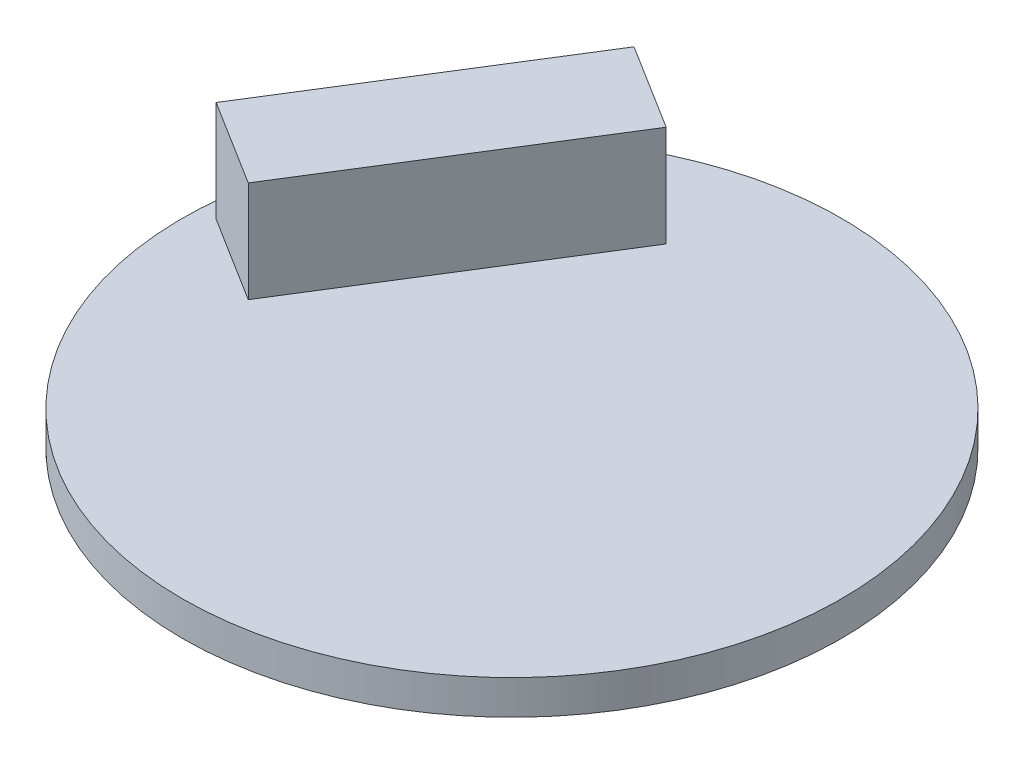
SolidWorks part; units mm, degrees
ref_plane "Front Plane" through (0, 0, 0) normal (0, 0, 1) x (1, 0, 0)
ref_plane "Top Plane" through (0, 0, 0) normal (0, 1, 0) x (1, 0, 0)
ref_plane "Right Plane" through (0, 0, 0) normal (1, 0, 0) x (0, 0, -1)
sketch "Sketch1" plane through (0, 0, 0) normal (0, 1, 0) x (1, 0, 0)
  circle A0 centre (0, 0) radius 16.3
  dimension "D1" = 32.6
extrude "Boss-Extrude1" add sketch "Sketch1" along normal blind 1.7
sketch "Sketch2" plane through (0, 1.7, 0) normal (0, 1, 0) x (1, 0, 0)
  line L0 (0, 0) -> (13.9928, -8.7437) construction
  line L5 (0, 0) -> (-13.9928, 8.7437) construction
  line L6 (-7.4743, 13.5143) -> (-15.423, 0.7935)
  line L7 (-15.423, 0.7935) -> (-11.1828, -1.856)
  line L8 (-11.1828, -1.856) -> (-3.234, 10.8647)
  line L9 (-3.234, 10.8647) -> (-7.4743, 13.5143)
  arc A0 (5.6331, -15.5087) -> (16.4085, 1.7356) centre (0, 0) ccw construction
  arc A1 (-5.6331, 15.5087) -> (-16.4085, -1.7356) centre (0, 0) ccw construction
  point P9 (12.2967, -7.6838)
  point P17 (-11.4486, 7.1539)
  point P20 (0, 0)
  point P21 (0, 0)
  dimension "D3" = 2
  dimension "D4" = 5
  dimension "D5" = 3
  dimension "D6" = 15
extrude "Boss-Extrude2" add sketch "Sketch2" along normal blind 5
sketch "Sketch3" plane through (-11.4486, 0, -7.1539) normal (-0.848, 0, -0.5299) x (-0.5299, 0, 0.848)
  line L0 (0, 1.7) -> (0, 6.7) construction
  line L1 (16.3, 1.7) -> (-16.3, 1.7) construction
  line L2 (-7.5, 6.7) -> (7.5, 6.7) construction
  line L3 (7.5, 6.7) -> (7.5, 1.7) construction
  line L4 (6.4562, 5.8076) -> (-6.4562, 5.8076)
  line L5 (6.4562, 5.8076) -> (6.4562, 2.5924)
  line L6 (6.4562, 2.5924) -> (-6.4562, 2.5924)
  line L7 (-6.4562, 5.8076) -> (-6.4562, 2.5924)
  line L8 (6.4562, 5.8076) -> (-6.4562, 2.5924) construction
  line L9 (6.4562, 2.5924) -> (-6.4562, 5.8076) construction
  point P6 (0, 4.2)
  dimension "D1" = 3.2153
  dimension "D2" = 1.0438
extrude "Cut-Extrude1" cut sketch "Sketch3" against normal blind 4
